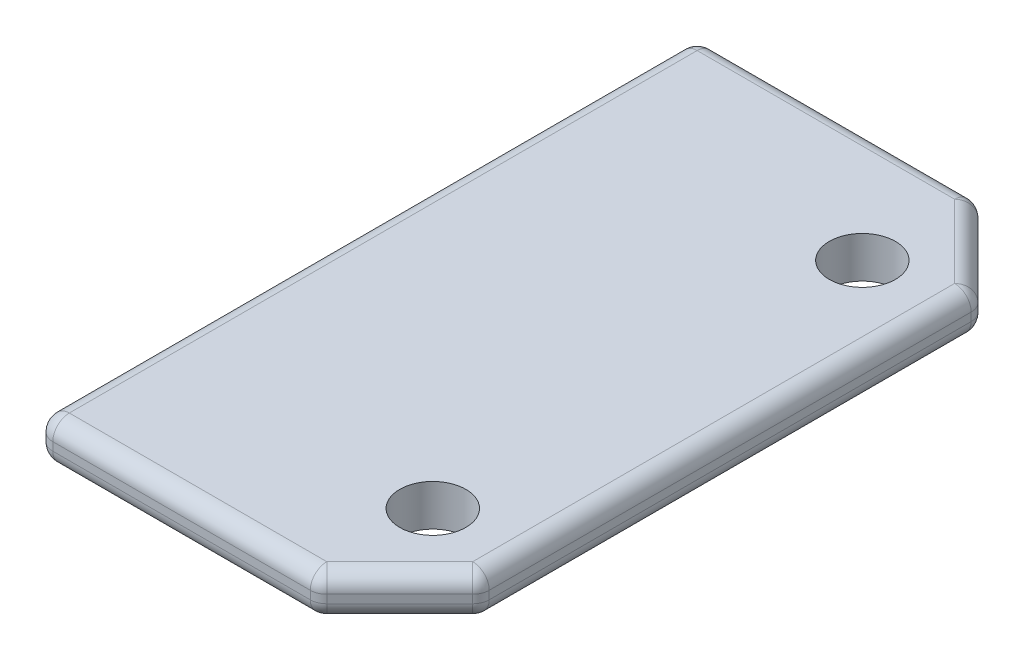
SolidWorks part; units mm, degrees
ref_plane "前视基准面" through (0, 0, 0) normal (0, 0, 1) x (1, 0, 0)
ref_plane "上视基准面" through (0, 0, 0) normal (0, 1, 0) x (1, 0, 0)
ref_plane "右视基准面" through (0, 0, 0) normal (1, 0, 0) x (0, 0, -1)
sketch "草图1" plane through (0, 0, 0) normal (0, 1, 0) x (1, 0, 0)
  line L0 (29.5548, 4.6418) -> (29.5548, 7.6418)
  line L1 (46.1406, 3.6418) -> (30.5548, 3.6418)
  line L2 (51.2619, 8.3489) -> (46.8477, 3.9347)
  line L3 (51.5548, 15.6418) -> (51.5548, 9.056)
  line L4 (51.5548, 38.2276) -> (51.5548, 31.6418)
  line L5 (46.8477, 43.3489) -> (51.2619, 38.9347)
  line L6 (30.5548, 43.6418) -> (46.1406, 43.6418)
  line L7 (29.5548, 7.6418) -> (29.5548, 42.6418)
  line L8 (51.5548, 31.6418) -> (51.5548, 15.6418)
  arc A0 (29.5548, 4.6418) -> (30.5548, 3.6418) centre (30.5548, 4.6418) ccw
  arc A1 (46.1406, 3.6418) -> (46.8477, 3.9347) centre (46.1406, 4.6418) ccw
  arc A2 (51.2619, 8.3489) -> (51.5548, 9.056) centre (50.5548, 9.056) ccw
  arc A3 (51.5548, 38.2276) -> (51.2619, 38.9347) centre (50.5548, 38.2276) ccw
  arc A4 (46.8477, 43.3489) -> (46.1406, 43.6418) centre (46.1406, 42.6418) ccw
  circle A5 centre (46.5548, 10.6418) radius 2
  circle A6 centre (46.5548, 36.6418) radius 2
  arc A7 (30.5548, 43.6418) -> (29.5548, 42.6418) centre (30.5548, 42.6418) ccw
  dimension "D1" = 1
extrude "凸台-拉伸1" add sketch "草图1" along normal blind 2.5
fillet "圆角1" radius 1 24 edges at (29.8477, 0, -3.9347) (38.3477, 0, -3.6418) (46.5232, 0, -3.7179) (49.0548, 0, -6.1418) (51.4786, 0, -8.6733) (51.5548, 0, -23.6418) (51.4786, 0, -38.6103) (49.0548, 0, -41.1418) (46.5232, 0, -43.5657) (38.3477, 0, -43.6418) (29.8477, 0, -43.3489) (29.5548, 0, -23.6418) (29.8477, 2.5, -43.3489) (38.3477, 2.5, -43.6418) (46.5232, 2.5, -43.5657) (49.0548, 2.5, -41.1418) (51.4786, 2.5, -38.6103) (51.5548, 2.5, -23.6418) (51.4786, 2.5, -8.6733) (49.0548, 2.5, -6.1418) (46.5232, 2.5, -3.7179) (38.3477, 2.5, -3.6418) (29.8477, 2.5, -3.9347) (29.5548, 2.5, -23.6418)
